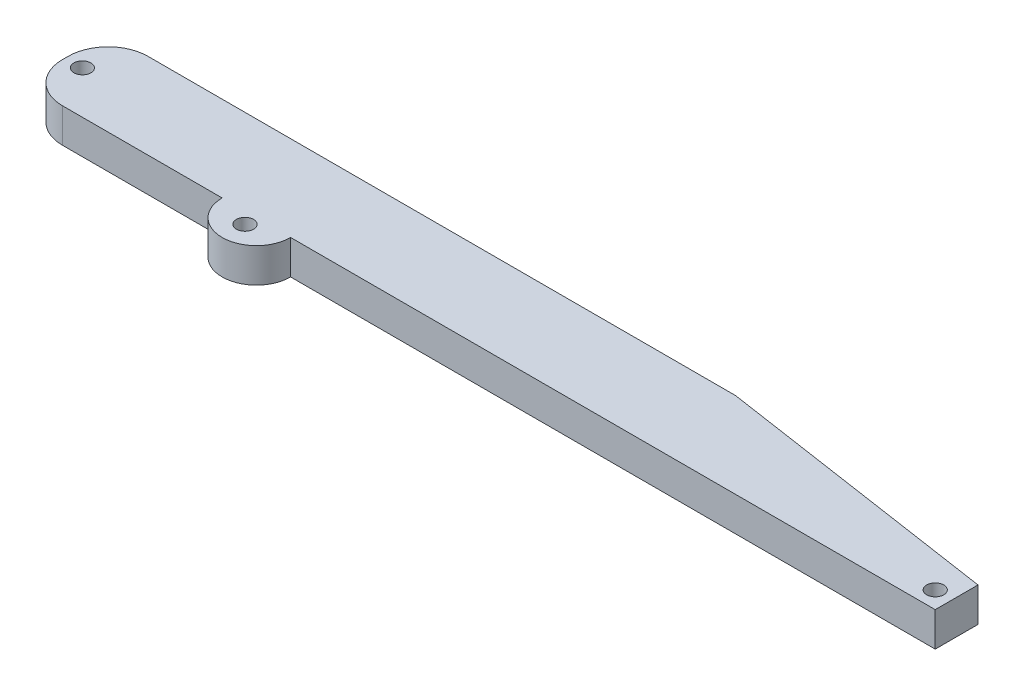
SolidWorks part; units mm, degrees
ref_plane "Front Plane" through (0, 0, 0) normal (0, 0, 1) x (1, 0, 0)
ref_plane "Top Plane" through (0, 0, 0) normal (0, 1, 0) x (1, 0, 0)
ref_plane "Right Plane" through (0, 0, 0) normal (1, 0, 0) x (0, 0, -1)
sketch "Sketch2" plane through (0, 0, 0) normal (0, 1, 0) x (1, 0, 0)
  line L11 (-80, 7.5) -> (80, 7.5)
  line L12 (-80, 7.5) -> (-80, -7.5)
  line L13 (-80, -7.5) -> (80, -7.5)
  line L14 (80, 7.5) -> (80, -7.5)
  dimension "D2" = 80
  dimension "D1" = 160
  dimension "D3" = 15
  dimension "D4" = 7.5
extrude "Boss-Extrude1" add sketch "Sketch2" along normal blind 6
sketch "Sketch4" plane through (0, 0, 0) normal (0, 1, 0) x (1, 0, 0)
  line L0 (-80, -7.5) -> (80, -7.5) construction
  line L1 (-45, -7.5) -> (-33, -7.5)
  arc A0 (-45, -7.5) -> (-33, -7.5) centre (-39, -7.5) ccw
  dimension "D1" = 6
  dimension "D2" = 35
  dimension "D3" = 12
extrude "Boss-Extrude2" add sketch "Sketch4" along normal blind 6
sketch "Sketch5" plane through (0, 6, 0) normal (0, 1, 0) x (1, 0, 0)
  line L0 (-80, -7.5) -> (-45, -7.5) construction
  line L1 (-80, 7.5) -> (-80, -7.5) construction
  line L2 (80, -7.5) -> (80, 7.5) construction
  line L3 (-33, -7.5) -> (80, -7.5) construction
  circle A0 centre (-77, 0) radius 1.5
  circle A1 centre (-39, -9.5) radius 1.5
  circle A2 centre (77, -4.5) radius 1.5
  arc A3 (-45, -7.5) -> (-33, -7.5) centre (-39, -7.5) ccw construction
  point P10 (-39, -13.5)
  dimension "D1" = 3
  dimension "D2" = 3
  dimension "D3" = 3
  dimension "D4" = 6
  dimension "D5" = 4
  dimension "D6" = 7.5
  dimension "D7" = 3
  dimension "D8" = 3
  dimension "D9" = 3
extrude "Cut-Extrude1" cut sketch "Sketch5" against normal through all
sketch "Sketch6" plane through (0, 6, 0) normal (0, 1, 0) x (1, 0, 0)
  line L0 (80, 0) -> (80, 7.5)
  line L1 (80, -7.5) -> (80, 7.5) construction
  line L2 (80, 7.5) -> (30, 7.5)
  line L3 (80, 7.5) -> (-80, 7.5) construction
  line L4 (30, 7.5) -> (80, 0)
  dimension "D1" = 50
extrude "Cut-Extrude2" cut sketch "Sketch6" against normal through all
fillet "Fillet1" radius 7 2 edges at (-80, 3, -7.5) (-80, 3, 7.5)
